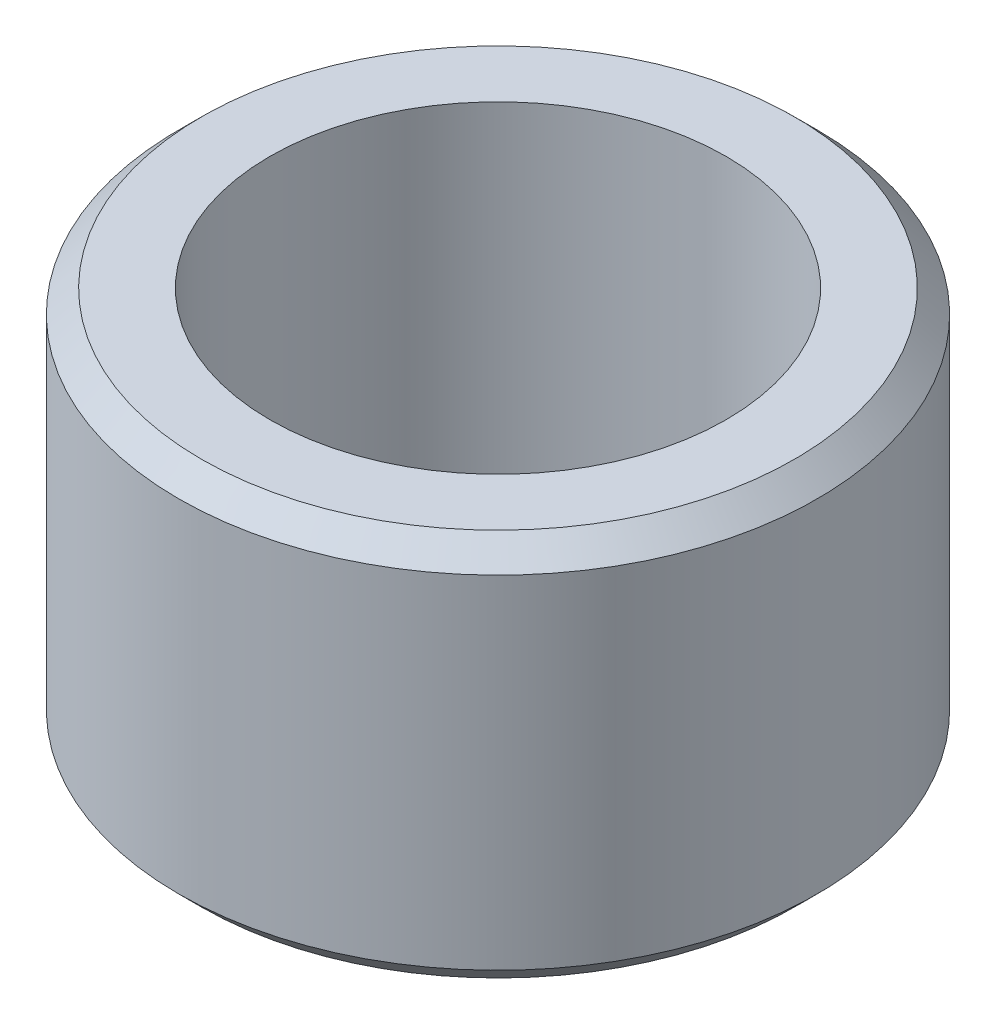
SolidWorks part; units mm, degrees
ref_plane "前视基准面" through (0, 0, 0) normal (0, 0, 1) x (1, 0, 0)
ref_plane "上视基准面" through (0, 0, 0) normal (0, 1, 0) x (1, 0, 0)
ref_plane "右视基准面" through (0, 0, 0) normal (1, 0, 0) x (0, 0, -1)
sketch "草图1" plane through (0, 0, 0) normal (0, 1, 0) x (1, 0, 0)
  circle A0 centre (0, 0) radius 5
  circle A1 centre (0, 0) radius 7
  dimension "D1" = 10
  dimension "D2" = 14
extrude "凸台-拉伸1" add sketch "草图1" along normal mid plane 8.5
chamfer "倒角1" distance 0.5 angle 45 2 edges at (0, -4.25, 7) (0, 4.25, 7)
